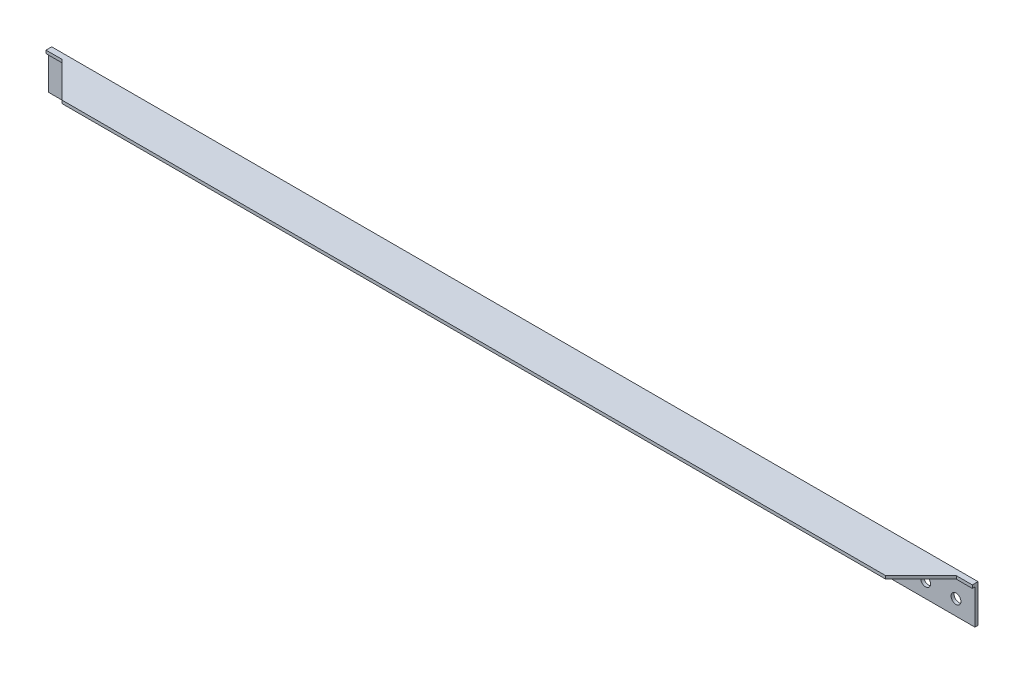
SolidWorks part; units mm, degrees
ref_plane "前视" through (0, 0, 0) normal (0, 0, 1) x (1, 0, 0)
ref_plane "上视" through (0, 0, 0) normal (0, 1, 0) x (1, 0, 0)
ref_plane "右视" through (0, 0, 0) normal (1, 0, 0) x (0, 0, -1)
sketch "草图1" plane through (0, 0, 0) normal (0, 0, 1) x (1, 0, 0)
  line L0 (0, 0) -> (0, 1201.1794) construction
  line L1 (-1220, 0) -> (1220, 0)
  line L2 (-1220, 0) -> (-1220, 100)
  line L3 (-1220, 100) -> (1220, 100)
  line L4 (1220, 0) -> (1220, 100)
  line L5 (1220, 40) -> (160, 40) construction
  line L6 (1220, 40) -> (80, 40) construction
  line L7 (0, 0) -> (1220, 0) construction
  line L8 (1170, 0) -> (1170, 100) construction
  line L9 (160, 100) -> (160, 40) construction
  line L10 (1090, 0) -> (1090, 100) construction
  line L11 (1414, 100) -> (1414, 0) construction
  line L12 (80, 40) -> (-1220, 40) construction
  line L13 (-1414, 582.7434) -> (-1414, -1649.9569) construction
  circle A0 centre (1090, 40) radius 13
  circle A1 centre (1170, 40) radius 13
  circle A2 centre (-1170, 40) radius 13
  circle A3 centre (-1090, 40) radius 13
  circle A4 centre (0, 40) radius 13
  circle A5 centre (80, 40) radius 13
  circle A6 centre (160, 40) radius 13
  circle A7 centre (-160, 40) radius 13
  circle A8 centre (-80, 40) radius 13
  dimension "D4" = 50
  dimension "D5" = 80
  dimension "D8" = 80
  dimension "D6" = 26
  dimension "D1" = 2440
  dimension "D2" = 100
  dimension "D3" = 40
  dimension "D7" = 80
  dimension "D9" = 244
  dimension "D10" = 244
extrude "基体-拉伸" add sketch "草图1" along normal blind 8
sketch "草图2" plane through (0, 0, 8) normal (0, 0, 1) x (1, 0, 0)
  line L0 (1220, 0) -> (1220, 100) construction
  line L1 (-1220, 100) -> (1220, 100)
  line L2 (-1220, 100) -> (-1220, 92)
  line L3 (-1220, 92) -> (1220, 92)
  line L4 (1220, 100) -> (1220, 92)
  dimension "D1" = 8
extrude "凸台-拉伸1" add sketch "草图2" along normal blind 100
sketch "草图3" plane through (0, 100, 0) normal (0, 1, 0) x (-1, 0, 0)
  line L2 (-1220, 108) -> (-1220, 0) construction
  line L3 (-1220, 0) -> (1220, 0) construction
  line L4 (-1220, 108) -> (1220, 108) construction
  line L5 (-1085, 108) -> (-1178, 15)
  line L6 (-1085, 108) -> (-1220, 108)
  line L7 (-1220, 108) -> (-1220, 15)
  line L8 (-1220, 15) -> (-1178, 15)
  line L9 (0, 868.9044) -> (0, -812.8803) construction
  line L10 (1220, 108) -> (1220, 0) construction
  line L11 (1220, 15) -> (1178, 15)
  line L12 (1220, 108) -> (1220, 15)
  line L13 (1085, 108) -> (1220, 108)
  line L14 (1085, 108) -> (1178, 15)
  point P0 (-1220, 15)
  point P5 (-1085, 108)
  dimension "D1" = 15
  dimension "D2" = 135
  dimension "D3" = 45
extrude "切除-拉伸1" cut sketch "草图3" against normal through all
